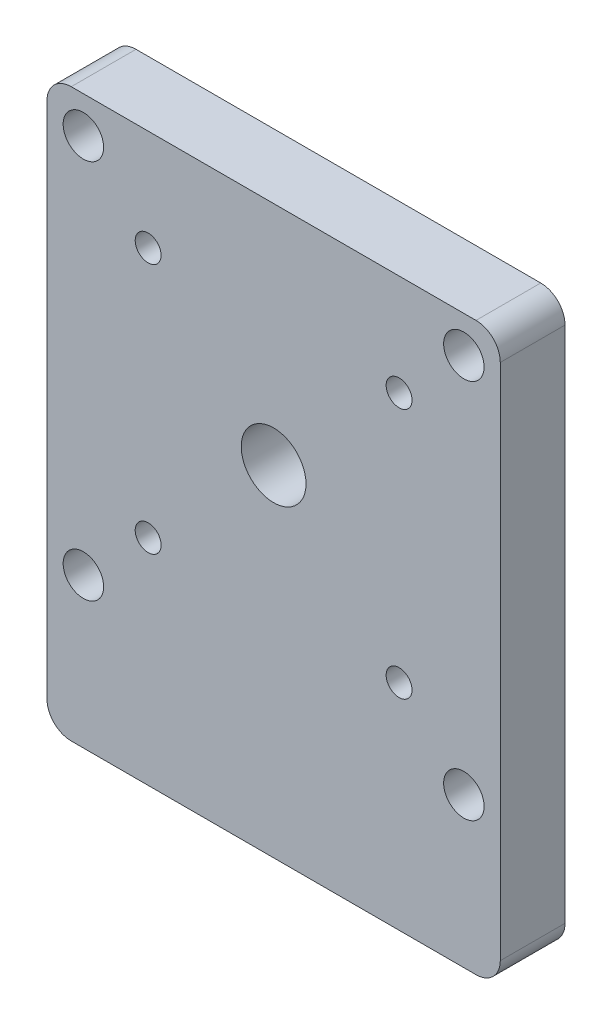
SolidWorks part; units mm, degrees
ref_plane "Front Plane" through (0, 0, 0) normal (0, 0, 1) x (1, 0, 0)
ref_plane "Top Plane" through (0, 0, 0) normal (0, 1, 0) x (1, 0, 0)
ref_plane "Right Plane" through (0, 0, 0) normal (1, 0, 0) x (0, 0, -1)
sketch "Sketch1" plane through (0, 0, 0) normal (0, 0, 1) x (1, 0, 0)
  line L1 (-28, -35) -> (28, -35)
  line L2 (-28, -35) -> (-28, 35)
  line L3 (-28, 35) -> (28, 35)
  line L4 (28, -35) -> (28, 35)
  line L5 (-28, -35) -> (28, 35) construction
  line L6 (-28, 35) -> (28, -35) construction
  point P0 (0, 0)
  dimension "D1" = 56
  dimension "D2" = 70
extrude "Boss-Extrude1" add sketch "Sketch1" along normal mid plane 8
sketch "Sketch2" plane through (0, 0, 4) normal (0, 0, 1) x (1, 0, 0)
  line L0 (0, 30.5) -> (0, 35) construction
  line L1 (-23.5, 30.5) -> (23.5, 30.5) construction
  line L2 (-23.5, 30.5) -> (-23.5, -16.5) construction
  line L3 (-23.5, -16.5) -> (23.5, -16.5) construction
  line L4 (23.5, 30.5) -> (23.5, -16.5) construction
  line L5 (-15.5, 22.5) -> (15.5, 22.5) construction
  line L6 (-15.5, 22.5) -> (-15.5, -8.5) construction
  line L7 (-15.5, -8.5) -> (15.5, -8.5) construction
  line L8 (15.5, 22.5) -> (15.5, -8.5) construction
  line L9 (28, 35) -> (-28, 35) construction
  line L10 (0, 22.5) -> (0, 30.5) construction
  line L11 (0, 7) -> (0, -35) construction
  line L12 (-28, -35) -> (28, -35) construction
  line L13 (15.5, 7) -> (0, 7) construction
  line L14 (0, 7) -> (-23.5, 7) construction
  circle A0 centre (-23.5, 30.5) radius 2.5
  circle A1 centre (23.5, 30.5) radius 2.5
  circle A2 centre (23.5, -16.5) radius 2.5
  circle A3 centre (-23.5, -16.5) radius 2.5
  circle A4 centre (0, 7) radius 4
  circle A5 centre (-15.5, 22.5) radius 1.6
  circle A6 centre (15.5, 22.5) radius 1.6
  circle A7 centre (15.5, -8.5) radius 1.6
  circle A8 centre (-15.5, -8.5) radius 1.6
  point P13 (0, 7)
  dimension "D4" = 5
  dimension "D5" = 8
  dimension "D6" = 3.2
  dimension "D1" = 47
  dimension "D2" = 31
  dimension "D3" = 42
extrude "Cut-Extrude1" cut sketch "Sketch2" against normal through all
fillet "Fillet1" radius 3 4 edges at (28, -35, 0) (-28, -35, 0) (-28, 35, 0) (28, 35, 0)
